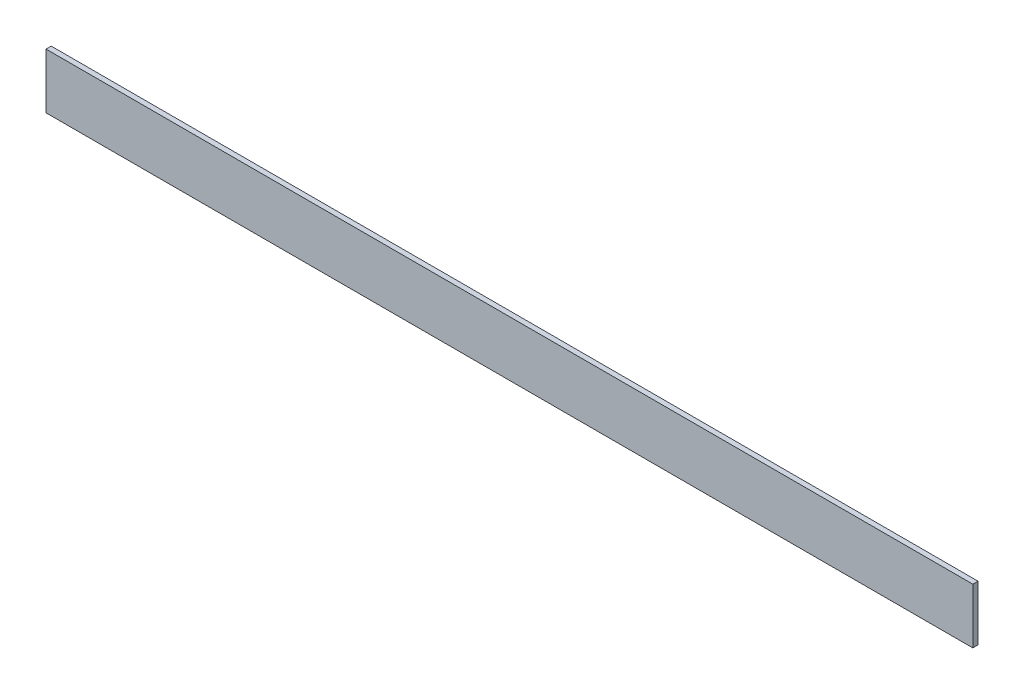
SolidWorks part; units mm, degrees
ref_plane "Front Plane" through (0, 0, 0) normal (0, 0, 1) x (1, 0, 0)
ref_plane "Top Plane" through (0, 0, 0) normal (0, 1, 0) x (1, 0, 0)
ref_plane "Right Plane" through (0, 0, 0) normal (1, 0, 0) x (0, 0, -1)
sketch "Sketch1" plane through (0, 0, 0) normal (0, 0, 1) x (1, 0, 0)
  line L1 (852.4875, -50.8) -> (-852.4875, -50.8)
  line L2 (852.4875, -50.8) -> (852.4875, 50.8)
  line L3 (852.4875, 50.8) -> (-852.4875, 50.8)
  line L4 (-852.4875, -50.8) -> (-852.4875, 50.8)
  line L5 (852.4875, -50.8) -> (-852.4875, 50.8) construction
  line L6 (852.4875, 50.8) -> (-852.4875, -50.8) construction
  point P0 (0, 0)
  dimension "D1" = 1704.975
  dimension "D2" = 101.6
extrude "Boss-Extrude1" add sketch "Sketch1" along normal blind 9.525
